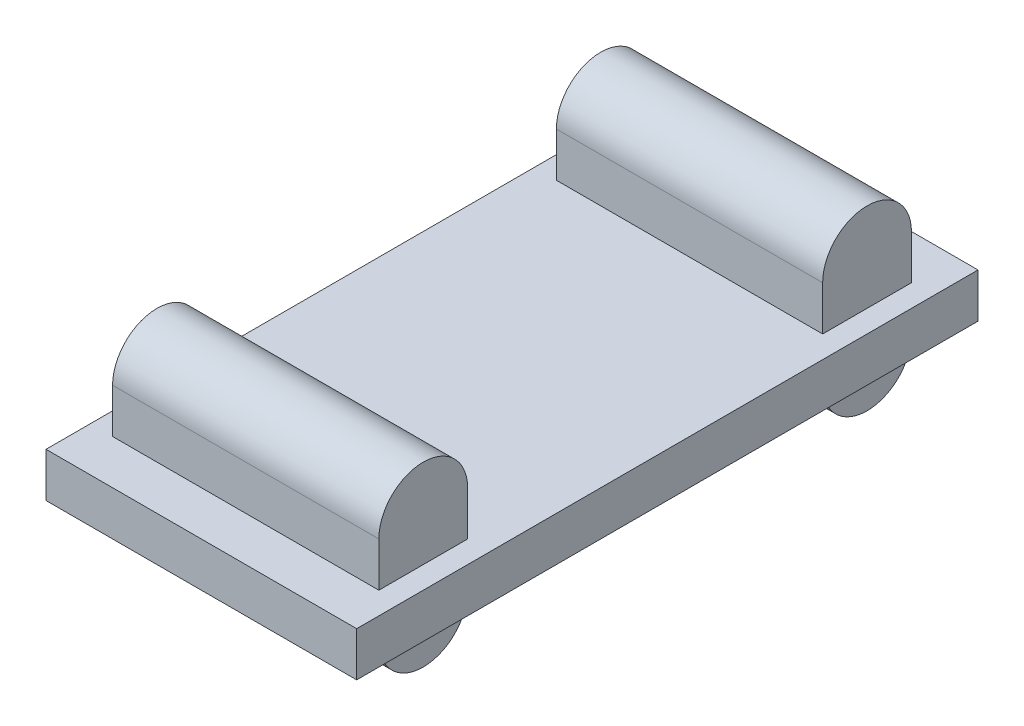
SolidWorks part; units mm, degrees
material "Plain Carbon Steel"
ref_plane "Front Plane" through (0, 0, 0) normal (0, 0, 1) x (1, 0, 0)
ref_plane "Top Plane" through (0, 0, 0) normal (0, 1, 0) x (1, 0, 0)
ref_plane "Right Plane" through (0, 0, 0) normal (1, 0, 0) x (0, 0, -1)
sketch "Sketch1" plane through (0, 0, 0) normal (0, 1, 0) x (1, 0, 0)
  line L1 (88.9, -177.8) -> (-88.9, -177.8)
  line L2 (88.9, -177.8) -> (88.9, 177.8)
  line L3 (88.9, 177.8) -> (-88.9, 177.8)
  line L4 (-88.9, -177.8) -> (-88.9, 177.8)
  line L5 (88.9, -177.8) -> (-88.9, 177.8) construction
  line L6 (88.9, 177.8) -> (-88.9, -177.8) construction
  point P0 (0, 0)
  dimension "D1" = 355.6
  dimension "D2" = 177.8
extrude "Boss-Extrude1" add sketch "Sketch1" along normal mid plane 25.4
sketch "Sketch2" plane through (0, 0, 0) normal (1, 0, 0) x (0, 0, -1)
  line L0 (-127, -12.7) -> (-127, 38.1) construction
  line L1 (-177.8, 12.7) -> (177.8, 12.7) construction
  line L2 (-152.4, -12.7) -> (-152.4, 38.1)
  line L3 (-101.6, -12.7) -> (-101.6, 38.1)
  line L4 (0, 55.88) -> (0, -55.88) construction
  line L5 (127, -12.7) -> (127, 38.1) construction
  line L6 (101.6, -12.7) -> (101.6, 38.1)
  line L7 (152.4, -12.7) -> (152.4, 38.1)
  arc A0 (-152.4, -12.7) -> (-101.6, -12.7) centre (-127, -12.7) ccw
  arc A1 (-101.6, 38.1) -> (-152.4, 38.1) centre (-127, 38.1) ccw
  arc A2 (101.6, -12.7) -> (152.4, -12.7) centre (127, -12.7) ccw
  arc A3 (152.4, 38.1) -> (101.6, 38.1) centre (127, 38.1) ccw
  point P4 (-127, 12.7)
  point P13 (127, 12.7)
  dimension "D1" = 50.8
  dimension "D2" = 101.6
  dimension "D3" = 127
  dimension "D4" = 127
extrude "Boss-Extrude2" add sketch "Sketch2" along normal mid plane 152.4
